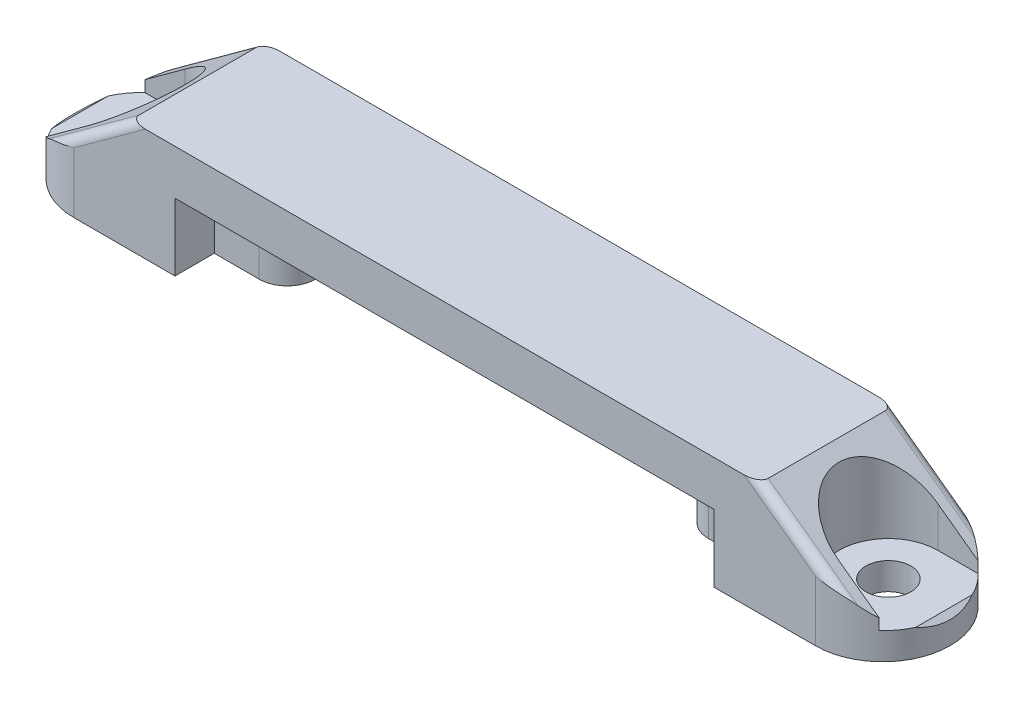
SolidWorks part; units mm, degrees
ref_plane "Ebene vorne" through (0, 0, 0) normal (0, 0, 1) x (1, 0, 0)
ref_plane "Ebene oben" through (0, 0, 0) normal (0, 1, 0) x (1, 0, 0)
ref_plane "Ebene rechts" through (0, 0, 0) normal (1, 0, 0) x (0, 0, -1)
sketch "Skizze1" plane through (0, 0, 0) normal (0, 0, 1) x (1, 0, 0)
  line L0 (0, 0) -> (7.5, 0)
  line L1 (7.5, 0) -> (7.5, 3)
  line L2 (7.5, 3) -> (31.5, 3)
  line L3 (31.5, 3) -> (31.5, 0)
  line L4 (31.5, 0) -> (39, 0)
  line L5 (39, 0) -> (39, 1)
  line L6 (39, 1) -> (33.5, 5)
  line L8 (33.5, 5) -> (5.5, 5)
  line L10 (5.5, 5) -> (0, 1)
  line L11 (0, 1) -> (0, 0)
  point P11 (5.5, 4.4344)
  point P12 (0, 0)
  dimension "D1" = 24
  dimension "D2" = 3
  dimension "D3" = 7.5
  dimension "D4" = 7.5
  dimension "D5" = 5
  dimension "D9" = 1
  dimension "D10" = 1
extrude "Aufsatz-Linear austragen1" add sketch "Skizze1" along normal blind 6
sketch "Skizze4" plane through (0, 0, 0) normal (0, -1, 0) x (1, 0, 0)
  line L0 (39, 6) -> (39, 0) construction
  line L1 (31.5, 0) -> (39, 0) construction
  circle A0 centre (36.25, 3) radius 1
  dimension "D1" = 2
  dimension "D3" = 3
  dimension "D2" = 2.75
extrude "Schnitt-Linear austragen1" cut sketch "Skizze4" against normal blind 3
ref_plane "Ebene1" through (0, 5, 0) normal (0, -1, 0) x (-1, 0, 0)
sketch "Skizze5" plane through (0, 5, 0) normal (0, -1, 0) x (-1, 0, 0)
  line L0 (-36.25, -5.2) -> (-39, -5.2)
  line L1 (-39, -6) -> (-39, 0) construction
  line L2 (-39, -5.2) -> (-39, -0.8)
  line L3 (-39, -0.8) -> (-36.25, -0.8)
  arc A0 (-36.25, -5.2) -> (-36.25, -0.8) centre (-36.25, -3) ccw
  dimension "D1" = 4.4
extrude "Schnitt-Linear austragen2" cut sketch "Skizze5" along normal blind 3.8
ref_plane "Ebene2" through (19.5, 0, 0) normal (-1, 0, 0) x (0, 0, 1)
mirror "Spiegeln1" about plane through (19.5, 0, 0) normal (-1, 0, 0) of "Schnitt-Linear austragen1", "Schnitt-Linear austragen2"
fillet "Verrundung1" radius 0.4 4 edges at (36.25, 3, 0) (36.25, 3, 6) (2.75, 3, 0) (2.75, 3, 6)
ref_plane "Ebene4" through (0, 0, 3) normal (0, 0, 1) x (1, 0, 0)
sketch "Skizze10" plane through (0, 5, 0) normal (0, -1, 0) x (-1, 0, 0)
  line L3 (-39, 0) -> (-39, -0.4) construction
  line L4 (-32.8199, 0) -> (-39, 0) construction
  line L5 (-39, -6) -> (-32.8199, -6) construction
  line L11 (-36, 0) -> (-39, 0)
  line L14 (-39.3385, 0) -> (-39.3385, -6)
  line L16 (-39, 0) -> (-39.3385, 0)
  line L17 (-36, -6) -> (-39.3385, -6)
  arc A1 (-36, -6) -> (-36, 0) centre (-36, -3) cw
  dimension "D3" = 3
  dimension "D2" = 3
extrude "Schnitt-Linear austragen6" cut sketch "Skizze10" along normal blind 6 contours L14 L17 A1 L11 L16
mirror "Spiegeln2" about plane through (19.5, 0, 0) normal (-1, 0, 0) of "Schnitt-Linear austragen6"
sketch "Skizze12" plane through (0, 3, 0) normal (0, -1, 0) x (1, 0, 0)
  line L0 (31.5, 1.75) -> (29.5, 1.75)
  line L1 (31.5, 6) -> (31.5, 0) construction
  line L2 (2.64, 3) -> (-2.64, 3) construction
  line L3 (29.5, 4.25) -> (31.5, 4.25)
  line L4 (31.5, 6) -> (31.5, 0) construction
  line L5 (31.5, 4.25) -> (31.5, 1.75)
  arc A0 (29.5, 1.75) -> (29.5, 4.25) centre (29.5, 3) cw
  dimension "D2" = 1.25
  dimension "D1" = 2
extrude "Aufsatz-Linear austragen2" add sketch "Skizze12" along normal blind 3
mirror "Spiegeln3" about plane through (19.5, 0, 0) normal (-1, 0, 0) of "Aufsatz-Linear austragen2"
